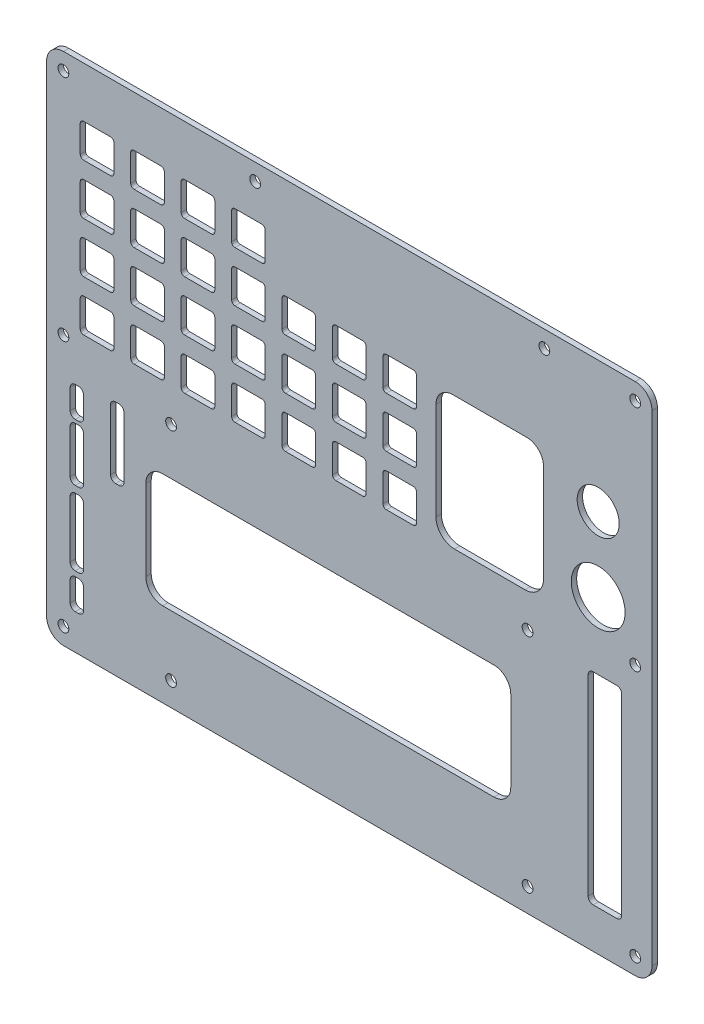
SolidWorks part; units mm, degrees
ref_plane "前视基准面" through (0, 0, 0) normal (0, 0, 1) x (1, 0, 0)
ref_plane "上视基准面" through (0, 0, 0) normal (0, 1, 0) x (1, 0, 0)
ref_plane "右视基准面" through (0, 0, 0) normal (1, 0, 0) x (0, 0, -1)
other "Configuration Table"
sketch "草图1" plane through (0, 0, 0) normal (0, 0, 1) x (1, 0, 0)
  line L1 (-85, 76.5) -> (85, 76.5)
  line L2 (-90, 71.5) -> (-90, -71.5)
  line L3 (-85, -76.5) -> (85, -76.5)
  line L4 (90, 71.5) -> (90, -71.5)
  line L5 (-90, 76.5) -> (90, -76.5) construction
  line L6 (-90, -76.5) -> (90, 76.5) construction
  arc A0 (-90, -71.5) -> (-85, -76.5) centre (-85, -71.5) ccw
  arc A1 (85, -76.5) -> (90, -71.5) centre (85, -71.5) ccw
  arc A2 (85, 76.5) -> (90, 71.5) centre (85, 71.5) cw
  arc A3 (-85, 76.5) -> (-90, 71.5) centre (-85, 71.5) ccw
  circle A4 centre (-85, 71.5) radius 1.6
  circle A5 centre (85, 71.5) radius 1.6
  circle A6 centre (85, -71.5) radius 1.6
  circle A7 centre (-85, -71.5) radius 1.6
  point P0 (0, 0)
  dimension "D3" = 5
  dimension "D4" = 3.2
  dimension "D1" = 180
  dimension "D2" = 153
extrude "凸台-拉伸1" add sketch "草图1" along normal blind 1.6
sketch "草图2" plane through (0, 0, 1.6) normal (0, 0, 1) x (1, 0, 0)
  line L1 (30.75, 46) -> (52.75, 46)
  line L2 (25.75, 41) -> (25.75, 12)
  line L3 (31.25, 6.5) -> (52.25, 6.5)
  line L4 (57.75, 41) -> (57.75, 12)
  line L5 (25.75, 46) -> (57.75, 6.5) construction
  line L6 (25.75, 6.5) -> (57.75, 46) construction
  arc A1 (25.75, 12) -> (31.25, 6.5) centre (31.25, 12) ccw
  arc A2 (52.25, 6.5) -> (57.75, 12) centre (52.25, 12) ccw
  arc A3 (52.75, 46) -> (57.75, 41) centre (52.75, 41) cw
  arc A4 (30.75, 46) -> (25.75, 41) centre (30.75, 41) ccw
  circle A7 centre (85, 71.5) radius 1.6 construction
  point P0 (41.75, 26.25)
  point P5 (54.15, 42.4)
  dimension "D3" = 5
  dimension "D5" = 5.5
  dimension "D4" = 3.6
  dimension "D6" = 3.6
  dimension "D8" = 29.1
  dimension "D1" = 32
  dimension "D2" = 39.5
  dimension "D7" = 30.85
extrude "切除-拉伸1" cut sketch "草图2" against normal up to next
sketch "草图3" plane through (0, 0, 1.6) normal (0, 0, 1) x (1, 0, 0)
  line L0 (-80, 30.5) -> (-80, 22.5)
  line L1 (-79, 16.5) -> (-71, 16.5)
  line L2 (-80, 15.5) -> (-80, 7.5)
  line L3 (-79, 6.5) -> (-71, 6.5)
  line L4 (-70, 15.5) -> (-70, 7.5)
  line L5 (-80, 16.5) -> (-70, 6.5) construction
  line L6 (-80, 6.5) -> (-70, 16.5) construction
  line L7 (-79, 31.5) -> (-71, 31.5)
  line L8 (-79, 21.5) -> (-71, 21.5)
  line L9 (-70, 30.5) -> (-70, 22.5)
  line L10 (-80, 45.5) -> (-80, 37.5)
  line L11 (-79, 46.5) -> (-71, 46.5)
  line L12 (-79, 36.5) -> (-71, 36.5)
  line L13 (-70, 45.5) -> (-70, 37.5)
  line L14 (-80, 60.5) -> (-80, 52.5)
  line L15 (-79, 61.5) -> (-71, 61.5)
  line L16 (-79, 51.5) -> (-71, 51.5)
  line L17 (-70, 60.5) -> (-70, 52.5)
  line L18 (-64, 16.5) -> (-56, 16.5)
  line L19 (-55, 15.5) -> (-55, 7.5)
  line L20 (-64, 6.5) -> (-56, 6.5)
  line L21 (-65, 15.5) -> (-65, 7.5)
  line L22 (-55, 30.5) -> (-55, 22.5)
  line L23 (-64, 21.5) -> (-56, 21.5)
  line L24 (-65, 30.5) -> (-65, 22.5)
  line L25 (-64, 31.5) -> (-56, 31.5)
  line L26 (-64, 36.5) -> (-56, 36.5)
  line L27 (-65, 45.5) -> (-65, 37.5)
  line L28 (-64, 46.5) -> (-56, 46.5)
  line L29 (-55, 45.5) -> (-55, 37.5)
  line L30 (-49, 16.5) -> (-41, 16.5)
  line L31 (-40, 15.5) -> (-40, 7.5)
  line L32 (-49, 6.5) -> (-41, 6.5)
  line L33 (-50, 15.5) -> (-50, 7.5)
  line L34 (-40, 30.5) -> (-40, 22.5)
  line L35 (-49, 21.5) -> (-41, 21.5)
  line L36 (-50, 30.5) -> (-50, 22.5)
  line L37 (-49, 31.5) -> (-41, 31.5)
  line L38 (-49, 36.5) -> (-41, 36.5)
  line L39 (-50, 45.5) -> (-50, 37.5)
  line L40 (-49, 46.5) -> (-41, 46.5)
  line L41 (-40, 45.5) -> (-40, 37.5)
  line L42 (-34, 16.5) -> (-26, 16.5)
  line L43 (-25, 15.5) -> (-25, 7.5)
  line L44 (-34, 6.5) -> (-26, 6.5)
  line L45 (-35, 15.5) -> (-35, 7.5)
  line L46 (-25, 30.5) -> (-25, 22.5)
  line L47 (-34, 21.5) -> (-26, 21.5)
  line L48 (-35, 30.5) -> (-35, 22.5)
  line L49 (-34, 31.5) -> (-26, 31.5)
  line L50 (-34, 36.5) -> (-26, 36.5)
  line L51 (-35, 45.5) -> (-35, 37.5)
  line L52 (-34, 46.5) -> (-26, 46.5)
  line L53 (-25, 45.5) -> (-25, 37.5)
  line L54 (-19, 16.5) -> (-11, 16.5)
  line L55 (-10, 15.5) -> (-10, 7.5)
  line L56 (-19, 6.5) -> (-11, 6.5)
  line L57 (-20, 15.5) -> (-20, 7.5)
  line L58 (-10, 30.5) -> (-10, 22.5)
  line L59 (-19, 21.5) -> (-11, 21.5)
  line L60 (-20, 30.5) -> (-20, 22.5)
  line L61 (-19, 31.5) -> (-11, 31.5)
  line L62 (-19, 36.5) -> (-11, 36.5)
  line L63 (-20, 45.5) -> (-20, 37.5)
  line L64 (-19, 46.5) -> (-11, 46.5)
  line L65 (-10, 45.5) -> (-10, 37.5)
  line L66 (-4, 16.5) -> (4, 16.5)
  line L67 (5, 15.5) -> (5, 7.5)
  line L68 (-4, 6.5) -> (4, 6.5)
  line L69 (-5, 15.5) -> (-5, 7.5)
  line L70 (5, 30.5) -> (5, 22.5)
  line L71 (-4, 21.5) -> (4, 21.5)
  line L72 (-5, 30.5) -> (-5, 22.5)
  line L73 (-4, 31.5) -> (4, 31.5)
  line L74 (-4, 36.5) -> (4, 36.5)
  line L75 (-5, 45.5) -> (-5, 37.5)
  line L76 (-4, 46.5) -> (4, 46.5)
  line L77 (5, 45.5) -> (5, 37.5)
  line L78 (11, 16.5) -> (19, 16.5)
  line L79 (20, 15.5) -> (20, 7.5)
  line L80 (11, 6.5) -> (19, 6.5)
  line L81 (10, 15.5) -> (10, 7.5)
  line L82 (20, 30.5) -> (20, 22.5)
  line L83 (11, 21.5) -> (19, 21.5)
  line L84 (10, 30.5) -> (10, 22.5)
  line L85 (11, 31.5) -> (19, 31.5)
  line L86 (11, 36.5) -> (19, 36.5)
  line L87 (10, 45.5) -> (10, 37.5)
  line L88 (11, 46.5) -> (19, 46.5)
  line L89 (20, 45.5) -> (20, 37.5)
  line L90 (-64, 51.5) -> (-56, 51.5)
  line L91 (-65, 60.5) -> (-65, 52.5)
  line L92 (-64, 61.5) -> (-56, 61.5)
  line L93 (-55, 60.5) -> (-55, 52.5)
  line L94 (-49, 51.5) -> (-41, 51.5)
  line L95 (-50, 60.5) -> (-50, 52.5)
  line L96 (-49, 61.5) -> (-41, 61.5)
  line L97 (-40, 60.5) -> (-40, 52.5)
  line L98 (-34, 51.5) -> (-26, 51.5)
  line L99 (-35, 60.5) -> (-35, 52.5)
  line L100 (-34, 61.5) -> (-26, 61.5)
  line L101 (-25, 60.5) -> (-25, 52.5)
  circle A0 centre (-85, 71.5) radius 1.6 construction
  arc A1 (-80, 52.5) -> (-79, 51.5) centre (-79, 52.5) ccw
  arc A2 (-80, 60.5) -> (-79, 61.5) centre (-79, 60.5) cw
  arc A3 (-71, 61.5) -> (-70, 60.5) centre (-71, 60.5) cw
  arc A4 (-71, 51.5) -> (-70, 52.5) centre (-71, 52.5) ccw
  arc A5 (-64, 51.5) -> (-65, 52.5) centre (-64, 52.5) cw
  arc A6 (-65, 60.5) -> (-64, 61.5) centre (-64, 60.5) cw
  arc A7 (-56, 61.5) -> (-55, 60.5) centre (-56, 60.5) cw
  arc A8 (-56, 51.5) -> (-55, 52.5) centre (-56, 52.5) ccw
  arc A9 (-41, 51.5) -> (-40, 52.5) centre (-41, 52.5) ccw
  arc A10 (-49, 51.5) -> (-50, 52.5) centre (-49, 52.5) cw
  arc A11 (-50, 60.5) -> (-49, 61.5) centre (-49, 60.5) cw
  arc A12 (-41, 61.5) -> (-40, 60.5) centre (-41, 60.5) cw
  arc A13 (-35, 60.5) -> (-34, 61.5) centre (-34, 60.5) cw
  arc A14 (-34, 51.5) -> (-35, 52.5) centre (-34, 52.5) cw
  arc A15 (-26, 61.5) -> (-25, 60.5) centre (-26, 60.5) cw
  arc A16 (-26, 51.5) -> (-25, 52.5) centre (-26, 52.5) ccw
  arc A17 (-56, 46.5) -> (-55, 45.5) centre (-56, 45.5) cw
  arc A18 (-56, 36.5) -> (-55, 37.5) centre (-56, 37.5) ccw
  arc A19 (-64, 36.5) -> (-65, 37.5) centre (-64, 37.5) cw
  arc A20 (-65, 45.5) -> (-64, 46.5) centre (-64, 45.5) cw
  arc A21 (-71, 46.5) -> (-70, 45.5) centre (-71, 45.5) cw
  arc A22 (-80, 45.5) -> (-79, 46.5) centre (-79, 45.5) cw
  arc A23 (-80, 37.5) -> (-79, 36.5) centre (-79, 37.5) ccw
  arc A24 (-71, 36.5) -> (-70, 37.5) centre (-71, 37.5) ccw
  arc A25 (-80, 22.5) -> (-79, 21.5) centre (-79, 22.5) ccw
  arc A26 (-80, 30.5) -> (-79, 31.5) centre (-79, 30.5) cw
  arc A27 (-71, 31.5) -> (-70, 30.5) centre (-71, 30.5) cw
  arc A28 (-71, 21.5) -> (-70, 22.5) centre (-71, 22.5) ccw
  arc A29 (-64, 21.5) -> (-65, 22.5) centre (-64, 22.5) cw
  arc A30 (-65, 30.5) -> (-64, 31.5) centre (-64, 30.5) cw
  arc A31 (-55, 30.5) -> (-56, 31.5) centre (-56, 30.5) ccw
  arc A32 (-55, 22.5) -> (-56, 21.5) centre (-56, 22.5) cw
  arc A33 (-34, 21.5) -> (-35, 22.5) centre (-34, 22.5) cw
  arc A34 (-25, 22.5) -> (-26, 21.5) centre (-26, 22.5) cw
  arc A35 (-25, 30.5) -> (-26, 31.5) centre (-26, 30.5) ccw
  arc A36 (-35, 30.5) -> (-34, 31.5) centre (-34, 30.5) cw
  arc A37 (-49, 21.5) -> (-50, 22.5) centre (-49, 22.5) cw
  arc A38 (-40, 22.5) -> (-41, 21.5) centre (-41, 22.5) cw
  arc A39 (-50, 30.5) -> (-49, 31.5) centre (-49, 30.5) cw
  arc A40 (-40, 30.5) -> (-41, 31.5) centre (-41, 30.5) ccw
  arc A41 (-41, 36.5) -> (-40, 37.5) centre (-41, 37.5) ccw
  arc A42 (-41, 46.5) -> (-40, 45.5) centre (-41, 45.5) cw
  arc A43 (-50, 45.5) -> (-49, 46.5) centre (-49, 45.5) cw
  arc A44 (-49, 36.5) -> (-50, 37.5) centre (-49, 37.5) cw
  arc A45 (-26, 36.5) -> (-25, 37.5) centre (-26, 37.5) ccw
  arc A46 (-34, 36.5) -> (-35, 37.5) centre (-34, 37.5) cw
  arc A47 (-35, 45.5) -> (-34, 46.5) centre (-34, 45.5) cw
  arc A48 (-26, 46.5) -> (-25, 45.5) centre (-26, 45.5) cw
  arc A49 (-11, 46.5) -> (-10, 45.5) centre (-11, 45.5) cw
  arc A50 (-20, 45.5) -> (-19, 46.5) centre (-19, 45.5) cw
  arc A51 (-19, 36.5) -> (-20, 37.5) centre (-19, 37.5) cw
  arc A52 (-11, 36.5) -> (-10, 37.5) centre (-11, 37.5) ccw
  arc A53 (-10, 30.5) -> (-11, 31.5) centre (-11, 30.5) ccw
  arc A54 (-20, 30.5) -> (-19, 31.5) centre (-19, 30.5) cw
  arc A55 (-19, 21.5) -> (-20, 22.5) centre (-19, 22.5) cw
  arc A56 (-10, 22.5) -> (-11, 21.5) centre (-11, 22.5) cw
  arc A57 (-4, 21.5) -> (-5, 22.5) centre (-4, 22.5) cw
  arc A58 (5, 22.5) -> (4, 21.5) centre (4, 22.5) cw
  arc A59 (5, 30.5) -> (4, 31.5) centre (4, 30.5) ccw
  arc A60 (-5, 30.5) -> (-4, 31.5) centre (-4, 30.5) cw
  arc A61 (-4, 36.5) -> (-5, 37.5) centre (-4, 37.5) cw
  arc A62 (-5, 45.5) -> (-4, 46.5) centre (-4, 45.5) cw
  arc A63 (4, 46.5) -> (5, 45.5) centre (4, 45.5) cw
  arc A64 (4, 36.5) -> (5, 37.5) centre (4, 37.5) ccw
  arc A65 (19, 36.5) -> (20, 37.5) centre (19, 37.5) ccw
  arc A66 (19, 46.5) -> (20, 45.5) centre (19, 45.5) cw
  arc A67 (10, 45.5) -> (11, 46.5) centre (11, 45.5) cw
  arc A68 (11, 36.5) -> (10, 37.5) centre (11, 37.5) cw
  arc A69 (10, 30.5) -> (11, 31.5) centre (11, 30.5) cw
  arc A70 (11, 21.5) -> (10, 22.5) centre (11, 22.5) cw
  arc A71 (20, 22.5) -> (19, 21.5) centre (19, 22.5) cw
  arc A72 (20, 30.5) -> (19, 31.5) centre (19, 30.5) ccw
  arc A73 (19, 16.5) -> (20, 15.5) centre (19, 15.5) cw
  arc A74 (20, 7.5) -> (19, 6.5) centre (19, 7.5) cw
  arc A75 (11, 6.5) -> (10, 7.5) centre (11, 7.5) cw
  arc A76 (11, 16.5) -> (10, 15.5) centre (11, 15.5) ccw
  arc A77 (4, 16.5) -> (5, 15.5) centre (4, 15.5) cw
  arc A78 (5, 7.5) -> (4, 6.5) centre (4, 7.5) cw
  arc A79 (-4, 6.5) -> (-5, 7.5) centre (-4, 7.5) cw
  arc A80 (-4, 16.5) -> (-5, 15.5) centre (-4, 15.5) ccw
  arc A81 (-11, 16.5) -> (-10, 15.5) centre (-11, 15.5) cw
  arc A82 (-10, 7.5) -> (-11, 6.5) centre (-11, 7.5) cw
  arc A83 (-19, 6.5) -> (-20, 7.5) centre (-19, 7.5) cw
  arc A84 (-19, 16.5) -> (-20, 15.5) centre (-19, 15.5) ccw
  arc A85 (-26, 16.5) -> (-25, 15.5) centre (-26, 15.5) cw
  arc A86 (-25, 7.5) -> (-26, 6.5) centre (-26, 7.5) cw
  arc A87 (-34, 6.5) -> (-35, 7.5) centre (-34, 7.5) cw
  arc A88 (-34, 16.5) -> (-35, 15.5) centre (-34, 15.5) ccw
  arc A89 (-41, 16.5) -> (-40, 15.5) centre (-41, 15.5) cw
  arc A90 (-40, 7.5) -> (-41, 6.5) centre (-41, 7.5) cw
  arc A91 (-49, 6.5) -> (-50, 7.5) centre (-49, 7.5) cw
  arc A92 (-49, 16.5) -> (-50, 15.5) centre (-49, 15.5) ccw
  arc A93 (-64, 6.5) -> (-65, 7.5) centre (-64, 7.5) cw
  arc A94 (-55, 7.5) -> (-56, 6.5) centre (-56, 7.5) cw
  arc A95 (-56, 16.5) -> (-55, 15.5) centre (-56, 15.5) cw
  arc A96 (-64, 16.5) -> (-65, 15.5) centre (-64, 15.5) ccw
  arc A97 (-80, 7.5) -> (-79, 6.5) centre (-79, 7.5) ccw
  arc A98 (-71, 6.5) -> (-70, 7.5) centre (-71, 7.5) ccw
  arc A99 (-71, 16.5) -> (-70, 15.5) centre (-71, 15.5) cw
  arc A100 (-79, 16.5) -> (-80, 15.5) centre (-79, 15.5) ccw
  point P0 (-75, 11.5)
  dimension "D1" = 60
  dimension "D2" = 10
  dimension "D8" = 1
  dimension "D3" = 10
  dimension "D4" = 10
  dimension "D5" = 4
  dimension "D6" = 7
  dimension "D7" = 4
extrude "切除-拉伸2" cut sketch "草图3" against normal up to next (1.6 mm away)
sketch "草图4" plane through (0, 0, 1.6) normal (0, 0, 1) x (1, 0, 0)
  line L0 (-85, 71.5) -> (85, 71.5) construction
  line L1 (-53, -69.5) -> (53, -69.5) construction
  line L2 (-53, -69.5) -> (-53, -3.5) construction
  line L3 (-53, -3.5) -> (53, -3.5) construction
  line L4 (53, -69.5) -> (53, -3.5) construction
  line L5 (-55.5, -51.5) -> (43, -51.5)
  line L6 (-60.5, -46.5) -> (-60.5, -22.5)
  line L7 (-55.5, -17.5) -> (43, -17.5)
  line L8 (48, -46.5) -> (48, -22.5)
  circle A0 centre (74, 15.5) radius 8
  circle A1 centre (-85, 3.5) radius 1.6
  circle A2 centre (-53, -69.5) radius 1.6
  circle A3 centre (-85, -71.5) radius 1.6 construction
  circle A4 centre (-53, -3.5) radius 1.6
  circle A5 centre (53, -3.5) radius 1.6
  circle A6 centre (53, -69.5) radius 1.6
  arc A7 (-55.5, -51.5) -> (-60.5, -46.5) centre (-55.5, -46.5) cw
  arc A8 (43, -51.5) -> (48, -46.5) centre (43, -46.5) ccw
  arc A9 (43, -17.5) -> (48, -22.5) centre (43, -22.5) cw
  arc A10 (-60.5, -22.5) -> (-55.5, -17.5) centre (-55.5, -22.5) cw
  circle A11 centre (74, 37.5) radius 6.25
  circle A12 centre (-85, 71.5) radius 1.6 construction
  circle A13 centre (85, 71.5) radius 1.6 construction
  circle A14 centre (85, 3.5) radius 1.6
  circle A15 centre (-28, 71.5) radius 1.6
  circle A16 centre (58, 71.5) radius 1.6
  dimension "D2" = 11
  dimension "D3" = 16
  dimension "D5" = 2
  dimension "D8" = 3.2
  dimension "D13" = 5
  dimension "D14" = 12.5
  dimension "D15" = 56
  dimension "D17" = 32
  dimension "D18" = 7
  dimension "D19" = 7
  dimension "D20" = 32
  dimension "D22" = 57
  dimension "D4" = 32
  dimension "D6" = 106
  dimension "D7" = 66
  dimension "D9" = 18
  dimension "D10" = 14
  dimension "D11" = 10
  dimension "D12" = 15
  dimension "D16" = 22
  dimension "D21" = 27
extrude "切除-拉伸3" cut sketch "草图4" against normal up to next
sketch "草图5" plane through (0, 0, 1.6) normal (0, 0, 1) x (1, 0, 0)
  line L1 (79.5, -64.5) -> (72.5, -64.5)
  line L2 (81, -63) -> (81, -6)
  line L3 (79.5, -4.5) -> (72.5, -4.5)
  line L4 (71, -63) -> (71, -6)
  line L25 (-81.5, -66) -> (-80.5, -66)
  line L26 (-83, -64.5) -> (-83, -58.5)
  line L27 (-81.5, -57) -> (-80.5, -57)
  line L28 (-79, -64.5) -> (-79, -58.5)
  line L29 (-83, -66) -> (-79, -57) construction
  line L30 (-83, -57) -> (-79, -66) construction
  line L31 (-81.5, -55.5) -> (-80.5, -55.5)
  line L32 (-83, -54) -> (-83, -37)
  line L33 (-81.5, -35.5) -> (-80.5, -35.5)
  line L34 (-79, -54) -> (-79, -37)
  line L35 (-83, -55.5) -> (-79, -35.5) construction
  line L36 (-83, -35.5) -> (-79, -55.5) construction
  line L37 (-81.5, -33.5) -> (-80.5, -33.5)
  line L38 (-83, -32) -> (-83, -19)
  line L39 (-81.5, -17.5) -> (-80.5, -17.5)
  line L40 (-79, -32) -> (-79, -19)
  line L41 (-83, -33.5) -> (-79, -17.5) construction
  line L42 (-83, -17.5) -> (-79, -33.5) construction
  line L43 (-81.5, -16.5) -> (-80.5, -16.5)
  line L44 (-83, -15) -> (-83, -9)
  line L45 (-81.5, -7.5) -> (-80.5, -7.5)
  line L46 (-79, -15) -> (-79, -9)
  line L47 (-83, -16.5) -> (-79, -7.5) construction
  line L48 (-83, -7.5) -> (-79, -16.5) construction
  line L49 (-69.5, -27) -> (-68.5, -27)
  line L50 (-71, -25.5) -> (-71, -7.5)
  line L51 (-69.5, -6) -> (-68.5, -6)
  line L52 (-67, -25.5) -> (-67, -7.5)
  line L53 (-71, -27) -> (-67, -6) construction
  line L54 (-71, -6) -> (-67, -27) construction
  circle A0 centre (85, -71.5) radius 1.6 construction
  arc A1 (72.5, -64.5) -> (71, -63) centre (72.5, -63) cw
  arc A2 (79.5, -64.5) -> (81, -63) centre (79.5, -63) ccw
  arc A3 (81, -6) -> (79.5, -4.5) centre (79.5, -6) ccw
  arc A4 (72.5, -4.5) -> (71, -6) centre (72.5, -6) ccw
  circle A5 centre (-85, -71.5) radius 1.6 construction
  arc A6 (-83, -58.5) -> (-81.5, -57) centre (-81.5, -58.5) cw
  arc A7 (-81.5, -66) -> (-83, -64.5) centre (-81.5, -64.5) cw
  arc A8 (-80.5, -66) -> (-79, -64.5) centre (-80.5, -64.5) ccw
  arc A9 (-80.5, -57) -> (-79, -58.5) centre (-80.5, -58.5) cw
  arc A10 (-80.5, -55.5) -> (-79, -54) centre (-80.5, -54) ccw
  arc A11 (-81.5, -55.5) -> (-83, -54) centre (-81.5, -54) cw
  arc A12 (-80.5, -35.5) -> (-79, -37) centre (-80.5, -37) cw
  arc A13 (-83, -37) -> (-81.5, -35.5) centre (-81.5, -37) cw
  arc A14 (-81.5, -33.5) -> (-83, -32) centre (-81.5, -32) cw
  arc A15 (-80.5, -33.5) -> (-79, -32) centre (-80.5, -32) ccw
  arc A16 (-80.5, -17.5) -> (-79, -19) centre (-80.5, -19) cw
  arc A17 (-83, -19) -> (-81.5, -17.5) centre (-81.5, -19) cw
  arc A18 (-81.5, -16.5) -> (-83, -15) centre (-81.5, -15) cw
  arc A19 (-80.5, -16.5) -> (-79, -15) centre (-80.5, -15) ccw
  arc A20 (-80.5, -7.5) -> (-79, -9) centre (-80.5, -9) cw
  arc A21 (-83, -9) -> (-81.5, -7.5) centre (-81.5, -9) cw
  arc A22 (-69.5, -27) -> (-71, -25.5) centre (-69.5, -25.5) cw
  arc A23 (-68.5, -27) -> (-67, -25.5) centre (-68.5, -25.5) ccw
  arc A24 (-68.5, -6) -> (-67, -7.5) centre (-68.5, -7.5) cw
  arc A25 (-71, -7.5) -> (-69.5, -6) centre (-69.5, -7.5) cw
  point P8 (71, -64.5)
  point P13 (81, -4.5)
  point P16 (71, -4.5)
  point P17 (-81, -61.5)
  point P22 (-81, -45.5)
  point P29 (-81, -12)
  point P42 (-81, -25.5)
  point P88 (-69, -16.5)
  dimension "D5" = 1.5
  dimension "D10" = 1.5
  dimension "D11" = 1.5
  dimension "D19" = 4
  dimension "D21" = 59.5
  dimension "D23" = 1.5
  dimension "D25" = 16
  dimension "D28" = 1.5
  dimension "D1" = 7
  dimension "D2" = 4
  dimension "D3" = 60
  dimension "D4" = 10
  dimension "D6" = 10
  dimension "D7" = 4
  dimension "D8" = 9
  dimension "D9" = 4
  dimension "D12" = 26
  dimension "D13" = 4
  dimension "D14" = 20
  dimension "D15" = 4
  dimension "D16" = 46
  dimension "D17" = 16
  dimension "D18" = 4
  dimension "D20" = 9
  dimension "D22" = 4
  dimension "D24" = 55
  dimension "D26" = 21
  dimension "D27" = 4
extrude "切除-拉伸4" cut sketch "草图5" against normal up to next
